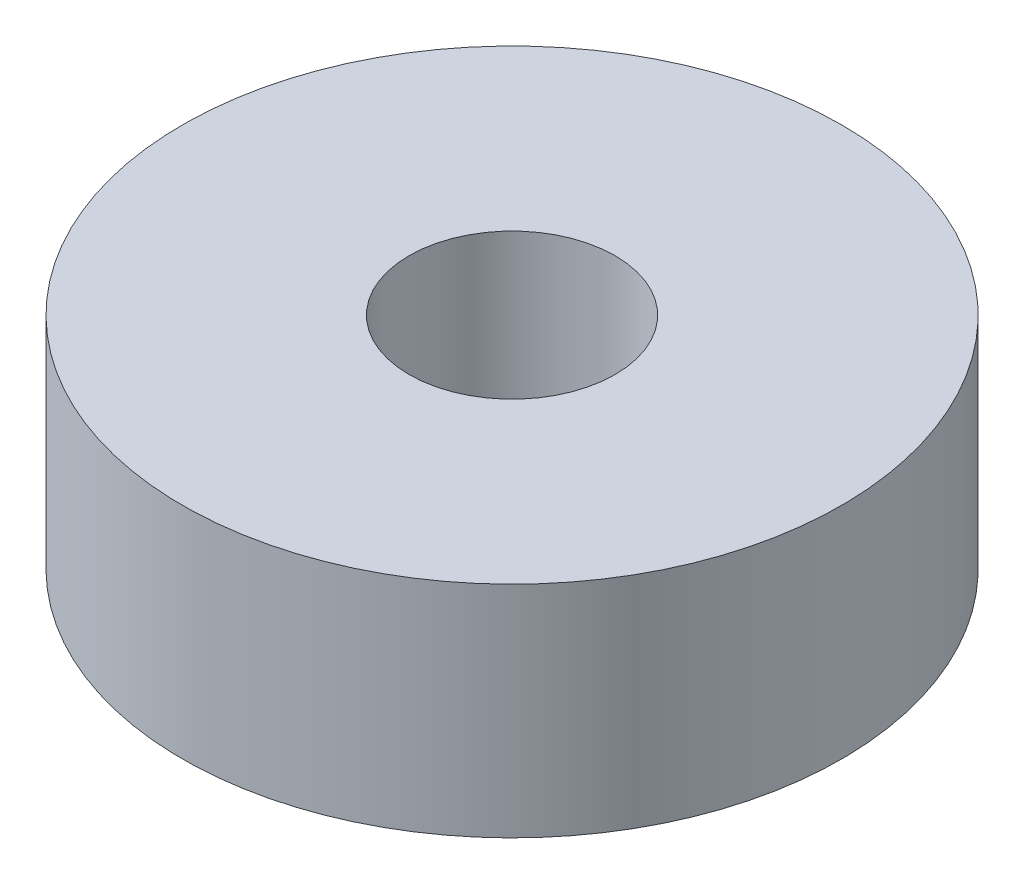
SolidWorks part; units mm, degrees
material "EPDM"
ref_plane "Front Plane" through (0, 0, 0) normal (0, 0, 1) x (1, 0, 0)
ref_plane "Top Plane" through (0, 0, 0) normal (0, 1, 0) x (1, 0, 0)
ref_plane "Right Plane" through (0, 0, 0) normal (1, 0, 0) x (0, 0, -1)
sketch "Sketch1" plane through (0, 0, 0) normal (0, 0, 1) x (1, 0, 0)
  line L0 (0, 0) -> (0, 32.8122) construction
  line L1 (-9.525, 0) -> (-9.525, 6.35)
  line L2 (-9.525, 6.35) -> (-2.9766, 6.35)
  line L3 (-2.9766, 6.35) -> (-2.9766, 1.5875)
  line L4 (-2.9766, 1.5875) -> (-1.5875, 1.5875)
  line L5 (-1.5875, 1.5875) -> (-1.5875, 0)
  line L6 (-1.5875, 0) -> (-9.525, 0)
  dimension "D1" = 19.05
  dimension "D2" = 6.35
  dimension "D3" = 3.175
  dimension "D4" = 5.9531
  dimension "D5" = 1.5875
revolve "Revolve1" add sketch "Sketch1" angle 360 about L0
